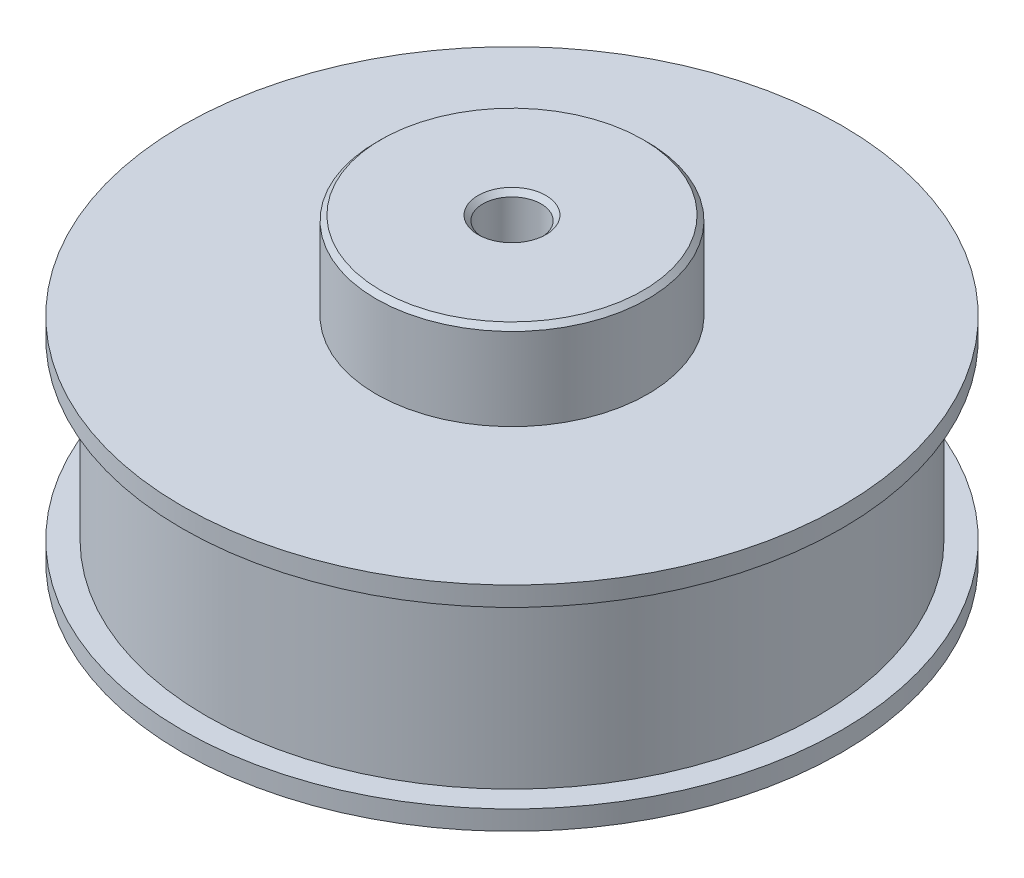
SolidWorks part; units mm, degrees
ref_plane "Front Plane" through (0, 0, 0) normal (0, 0, 1) x (1, 0, 0)
ref_plane "Top Plane" through (0, 0, 0) normal (0, 1, 0) x (1, 0, 0)
ref_plane "Right Plane" through (0, 0, 0) normal (1, 0, 0) x (0, 0, -1)
sketch "Sketch1" plane through (0, 0, 0) normal (0, 1, 0) x (1, 0, 0)
  circle A0 centre (0, 0) radius 34
  dimension "D1" = 68
extrude "Boss-Extrude1" add sketch "Sketch1" along normal blind 22
sketch "Sketch2" plane through (0, 22, 0) normal (0, 1, 0) x (1, 0, 0)
  circle A1 centre (0, 0) radius 31.5
  circle A2 centre (0, 0) radius 34
  circle A3 centre (0, 0) radius 34
  dimension "D2" = 63
  dimension "D1" = 0
extrude "Cut-Extrude1" cut sketch "Sketch2" against normal offset from surface (18 mm away) 2 from offset 2 up to face at (0, 0, 34) offset against normal yes
sketch "Sketch3" plane through (0, 22, 0) normal (0, 1, 0) x (1, 0, 0)
  circle A0 centre (0, 0) radius 14
  dimension "D1" = 28
extrude "Boss-Extrude2" add sketch "Sketch3" along normal blind 9
chamfer "Chamfer1" distance 0.5 angle 45 1 edges at (0, 31, 14)
sketch "Sketch4" plane through (0, 31, 0) normal (0, 1, 0) x (1, 0, 0)
  circle A0 centre (0, 0) radius 3
  dimension "D1" = 6
extrude "Cut-Extrude2" cut sketch "Sketch4" against normal up to surface (31 mm away) up to face at (0, 0, 34)
chamfer "Chamfer2" distance 0.5 angle 45 1 edges at (0, 31, 3)
